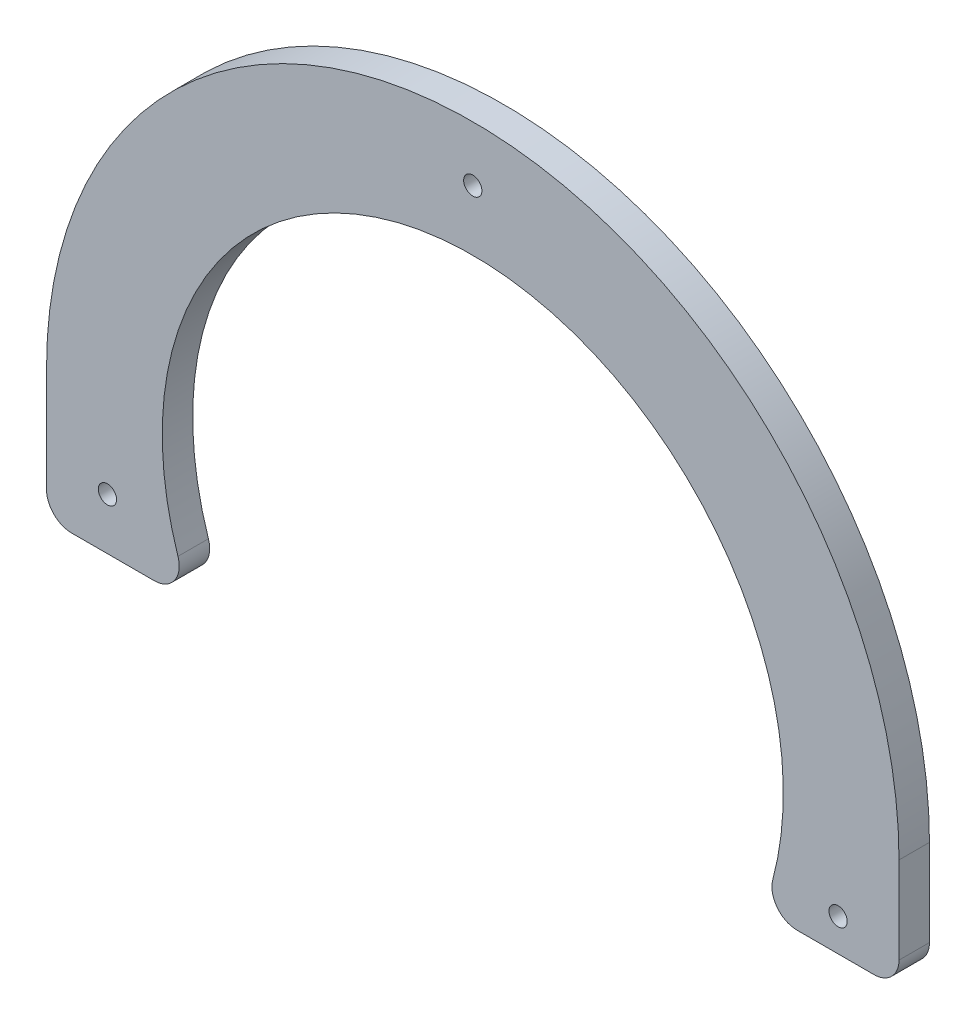
SolidWorks part; units mm, degrees
material "6063-O"
ref_plane "Front Plane" through (0, 0, 0) normal (0, 0, 1) x (1, 0, 0)
ref_plane "Top Plane" through (0, 0, 0) normal (0, 1, 0) x (1, 0, 0)
ref_plane "Right Plane" through (0, 0, 0) normal (1, 0, 0) x (0, 0, -1)
sketch "Sketch1" plane through (0, 0, 0) normal (0, 0, 1) x (1, 0, 0)
  line L22 (-43.1605, 10.4219) -> (-55.7931, 10.4219)
  line L23 (-174.9205, 7.3427) -> (-161.3672, 7.3427)
  line L26 (-179.0405, 11.4627) -> (-179.0405, 28.787)
  line L28 (-39.0405, 14.5412) -> (-39.0405, 28.787)
  circle A27 centre (-169.0405, 15.7833) radius 1.5
  circle A28 centre (-49.0405, 15.7833) radius 1.5
  arc A32 (-59.7731, 15.6067) -> (-157.456, 12.7576) centre (-109.0405, 28.787) ccw
  arc A33 (-174.9205, 7.3427) -> (-179.0405, 11.4627) centre (-174.9205, 11.4627) cw
  arc A34 (-43.1605, 10.4219) -> (-39.0405, 14.5412) centre (-43.1605, 14.5419) ccw
  arc A35 (-39.0405, 28.787) -> (-179.0405, 28.787) centre (-109.0405, 28.787) ccw
  arc A37 (-59.7731, 15.6067) -> (-55.7931, 10.4219) centre (-55.7931, 14.5419) ccw
  arc A38 (-157.456, 12.7576) -> (-161.3672, 7.3427) centre (-161.3672, 11.4627) cw
  circle A39 centre (-109.0405, 89.7039) radius 1.5
  dimension "D1" = 102
  dimension "D2" = 8.4406
  dimension "D4" = 4.12
  dimension "D5" = 4.12
  dimension "D7" = 120
  dimension "D8" = 60
  dimension "D3" = 4.12
  dimension "D6" = 70
  dimension "D9" = 3
extrude "Yükseklik-Ekstrüzyon1" add sketch "Sketch1" along normal mid plane 5
